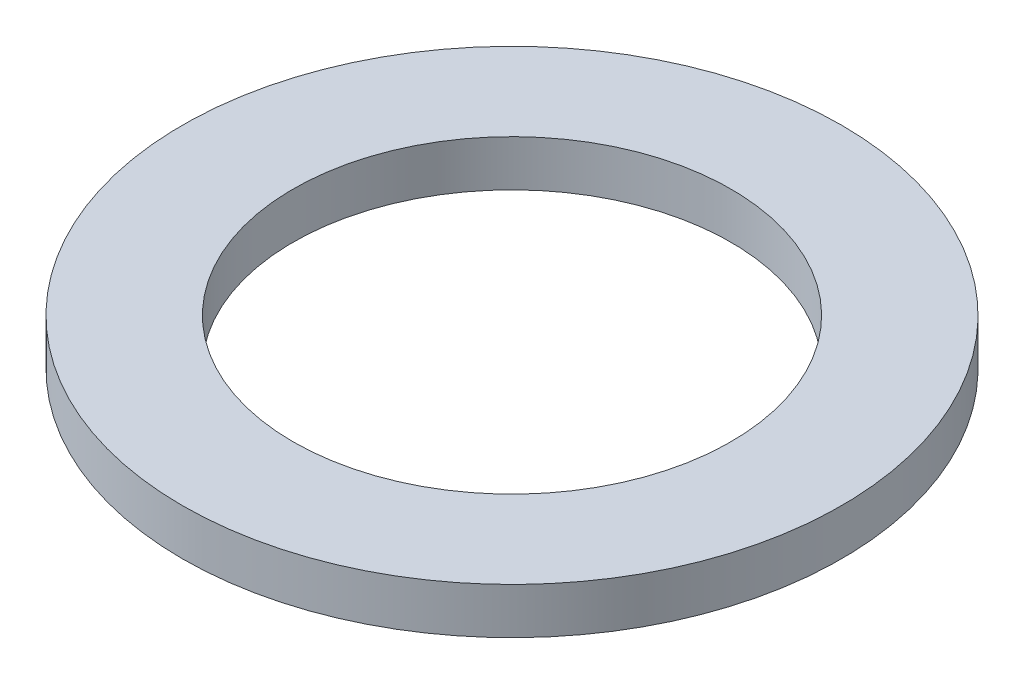
SolidWorks part; units mm, degrees
ref_plane "前视基准面" through (0, 0, 0) normal (0, 0, 1) x (1, 0, 0)
ref_plane "上视基准面" through (0, 0, 0) normal (0, 1, 0) x (1, 0, 0)
ref_plane "右视基准面" through (0, 0, 0) normal (1, 0, 0) x (0, 0, -1)
sketch "草图1" plane through (0, 0, 0) normal (0, 1, 0) x (1, 0, 0)
  circle A0 centre (0, 0) radius 4.75
  circle A1 centre (0, 0) radius 7.15
  dimension "D1" = 9.5
  dimension "D2" = 14.3
extrude "凸台-拉伸1" add sketch "草图1" along normal blind 1
